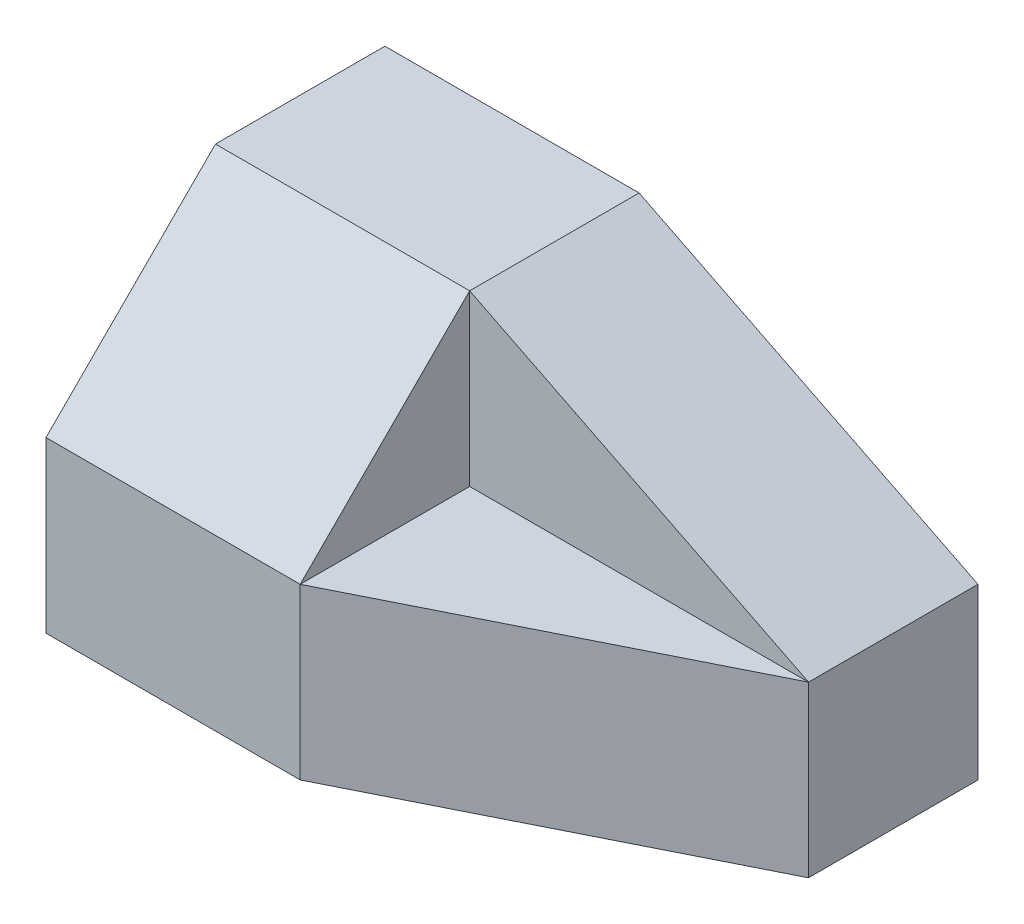
SolidWorks part; units mm, degrees
ref_plane "前基準面" through (0, 0, 0) normal (0, 0, 1) x (1, 0, 0)
ref_plane "上基準面" through (0, 0, 0) normal (0, 1, 0) x (1, 0, 0)
ref_plane "右基準面" through (0, 0, 0) normal (1, 0, 0) x (0, 0, -1)
sketch "草圖1" plane through (0, 0, 0) normal (0, 1, 0) x (1, 0, 0)
  line L0 (0, 0) -> (0, 4)
  line L1 (0, 4) -> (7, 4)
  line L2 (7, 4) -> (7, 2)
  line L3 (7, 2) -> (3, 0)
  line L4 (3, 0) -> (0, 0)
  dimension "D1" = 4
  dimension "D2" = 7
  dimension "D3" = 2
  dimension "D4" = 3
extrude "填料-伸長1" add sketch "草圖1" along normal blind 2
sketch "草圖3" plane through (0, 0, 0) normal (-1, 0, 0) x (0, 0, 1)
  line L0 (-4, 2) -> (-4, 4)
  line L1 (-4, 4) -> (-2, 4)
  line L2 (-2, 4) -> (-2, 2)
  line L3 (-4, 2) -> (0, 2) construction
  line L4 (-2, 2) -> (-4, 2)
  dimension "D1" = 2
extrude "填料-伸長2" add sketch "草圖3" against normal blind 3
sketch "草圖4" plane through (0, 0, -4) normal (0, 0, -1) x (-1, 0, 0)
  line L0 (-7, 2) -> (-3, 4)
  line L1 (-3, 4) -> (-3, 2)
  line L2 (-3, 2) -> (-7, 2)
extrude "填料-伸長3" add sketch "草圖4" against normal blind 2
sketch "草圖5" plane through (0, 0, 0) normal (-1, 0, 0) x (0, 0, 1)
  line L0 (-2, 4) -> (0, 2)
  line L1 (0, 2) -> (-2, 2)
  line L2 (-2, 2) -> (-2, 4)
extrude "填料-伸長4" add sketch "草圖5" against normal blind 3
